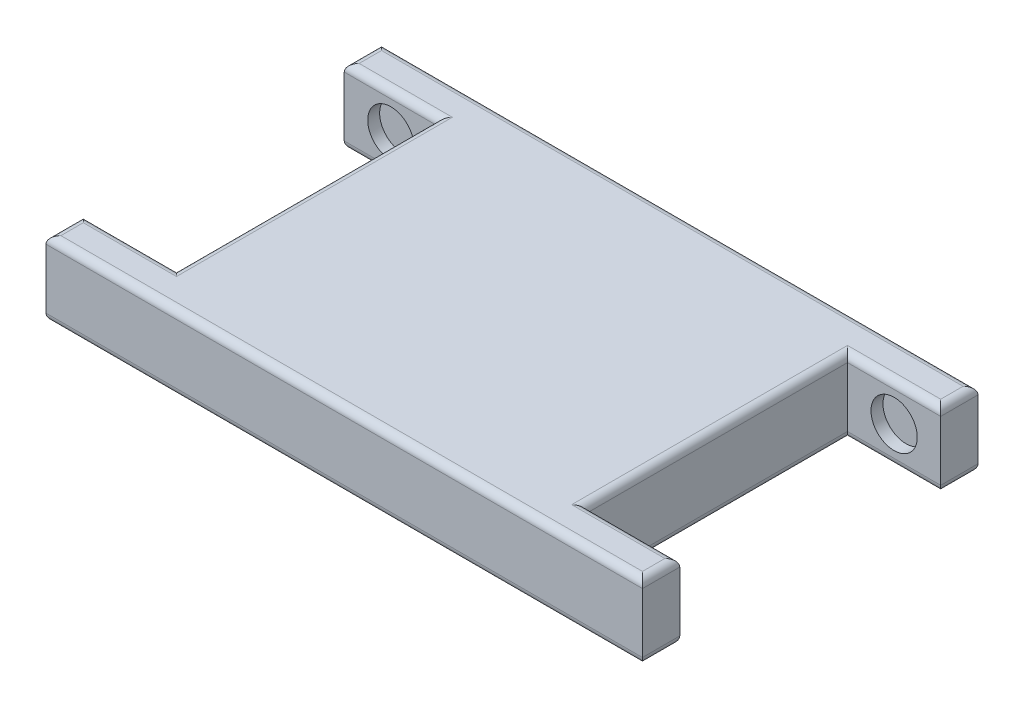
SolidWorks part; units mm, degrees
material "Oak"
ref_plane "Front Plane" through (0, 0, 0) normal (0, 0, 1) x (1, 0, 0)
ref_plane "Top Plane" through (0, 0, 0) normal (0, 1, 0) x (1, 0, 0)
ref_plane "Right Plane" through (0, 0, 0) normal (1, 0, 0) x (0, 0, -1)
sketch "Sketch2" plane through (0, 0, 0) normal (0, 1, 0) x (1, 0, 0)
  line L1 (-163.9124, 242.9732) -> (386.0876, 242.9732)
  line L2 (-163.9124, 242.9732) -> (-163.9124, -207.0268)
  line L3 (-163.9124, -207.0268) -> (386.0876, -207.0268)
  line L4 (386.0876, 242.9732) -> (386.0876, -207.0268)
  dimension "D1" = 550
  dimension "D2" = 450
extrude "Boss-Extrude1" add sketch "Sketch2" along normal blind 100
sketch "Sketch3" plane through (-163.9124, 0, 0) normal (-1, 0, 0) x (0, 0, 1)
  line L0 (207.0268, 0) -> (-242.9732, 0) construction
  line L1 (-242.9732, 100) -> (-192.9732, 100)
  line L2 (-242.9732, 100) -> (-242.9732, 0)
  line L3 (-242.9732, 0) -> (-192.9732, 0)
  line L4 (-192.9732, 100) -> (-192.9732, 0)
  dimension "D1" = 50
extrude "Boss-Extrude2" add sketch "Sketch3" along normal blind 125
ref_plane "Plane1" through (0, 0, -17.9732) normal (0, 0, -1) x (-1, 0, 0)
mirror "Mirror1" about plane through (0, 0, -17.9732) normal (0, 0, -1) of "Boss-Extrude1", "Boss-Extrude2"
ref_plane "Plane2" through (111.0876, 0, 0) normal (1, 0, 0) x (0, 0, -1)
mirror "Mirror2" about plane through (111.0876, 0, 0) normal (1, 0, 0) of "Mirror1", "Boss-Extrude1", "Boss-Extrude2"
sketch "Sketch4" plane through (0, 0, 157.0268) normal (0, 0, -1) x (-1, 0, 0)
  circle A0 centre (-448.5876, 50) radius 31
  dimension "D1" = 62
extrude "Cut-Extrude1" cut sketch "Sketch4" against normal blind 16
mirror "Mirror3" about plane through (0, 0, -17.9732) normal (0, 0, -1) of "Cut-Extrude1"
mirror "Mirror4" about plane through (111.0876, 0, 0) normal (1, 0, 0) of "Mirror3", "Cut-Extrude1"
fillet "Fillet4" radius 10 24 edges at (-226.4124, 0, -192.9732) (-163.9124, 0, -17.9732) (-163.9124, 100, -17.9732) (-226.4124, 0, 157.0268) (-226.4124, 100, 157.0268) (-288.9124, 100, 182.0268) (-288.9124, 0, 182.0268) (111.0876, 0, 207.0268) (111.0876, 100, 207.0268) (511.0876, 0, 182.0268) (511.0876, 100, 182.0268) (448.5876, 100, 157.0268) (448.5876, 0, 157.0268) (386.0876, 0, -17.9732) (386.0876, 100, -17.9732) (448.5876, 0, -192.9732) (448.5876, 100, -192.9732) (511.0876, 100, -217.9732) (511.0876, 0, -217.9732) (111.0876, 100, -242.9732) (111.0876, 0, -242.9732) (-288.9124, 0, -217.9732) (-226.4124, 100, -192.9732) (-288.9124, 100, -217.9732)
